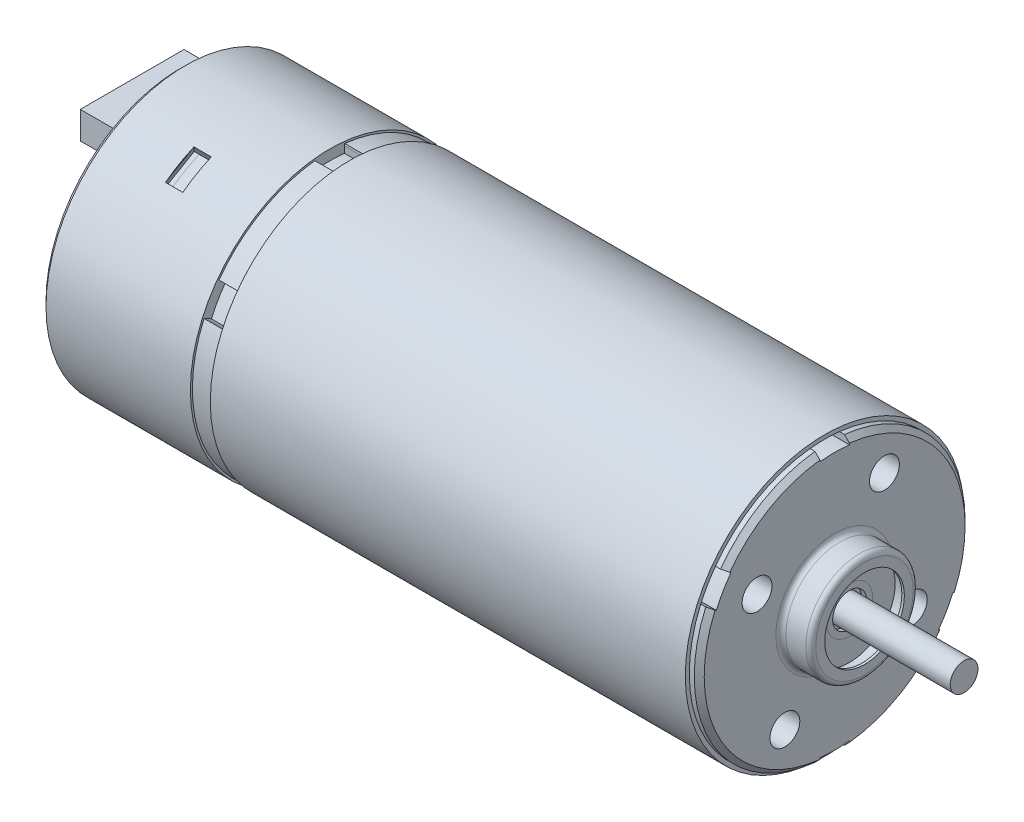
SolidWorks part; units mm, degrees
ref_plane "Front Plane" through (0, 0, 0) normal (0, 0, 1) x (1, 0, 0)
ref_plane "Top Plane" through (0, 0, 0) normal (0, 1, 0) x (1, 0, 0)
ref_plane "Right Plane" through (0, 0, 0) normal (1, 0, 0) x (0, 0, -1)
sketch "Sketch1" plane through (0, 0, 0) normal (1, 0, 0) x (0, 0, -1)
  circle A0 centre (0, 0) radius 13.6
extrude "Boss-Extrude1" add sketch "Sketch1" against normal blind 50.7
sketch "Sketch2" plane through (0, 0, 0) normal (1, 0, 0) x (0, 0, -1)
  line L0 (0, 0) -> (0, 13.6) construction
  line L1 (0, 0) -> (-13.6, 0) construction
  line L3 (-1.4767, 12.8723) -> (-1.4767, 14.3728)
  line L4 (-1.4767, 14.3728) -> (1.4767, 14.3728)
  line L5 (1.4767, 12.8723) -> (1.4767, 14.3728)
  line L6 (-1.3673, 12.8844) -> (1.4767, 14.3728) construction
  line L7 (-1.4767, 14.3728) -> (1.3673, 12.8844) construction
  line L8 (-1.4767, -14.3728) -> (1.3673, -12.8844) construction
  line L9 (-1.3673, -12.8844) -> (1.4767, -14.3728) construction
  line L10 (1.4767, -12.8723) -> (1.4767, -14.3728)
  line L11 (-1.4767, -14.3728) -> (1.4767, -14.3728)
  line L12 (-1.4767, -12.8723) -> (-1.4767, -14.3728)
  line L13 (11.8861, -5.1574) -> (13.1855, -5.9076)
  line L14 (13.1855, -5.9076) -> (11.7089, -8.4652)
  line L15 (10.4095, -7.715) -> (11.7089, -8.4652)
  line L16 (-11.8861, 5.1574) -> (-13.1855, 5.9076)
  line L17 (-11.7089, 8.4652) -> (-13.1855, 5.9076)
  line L18 (-10.4095, 7.715) -> (-11.7089, 8.4652)
  line L19 (0, 0) -> (11.7779, -6.8) construction
  line L20 (11.8419, -5.2581) -> (11.7089, -8.4652) construction
  line L21 (13.1855, -5.9076) -> (10.4746, -7.6263) construction
  line L22 (-11.7089, 8.4652) -> (-11.8419, 5.2581) construction
  line L23 (-10.4746, 7.6263) -> (-13.1855, 5.9076) construction
  circle A0 centre (0, 0) radius 13.6 construction
  arc A1 (1.4767, 12.8723) -> (-1.4767, 12.8723) centre (0, 0) ccw
  arc A2 (1.4767, -12.8723) -> (-1.4767, -12.8723) centre (0, 0) cw
  arc A3 (10.4095, -7.715) -> (11.8861, -5.1574) centre (0, 0) ccw
  arc A4 (-11.8861, 5.1574) -> (-10.4095, 7.715) centre (0, 0) cw
  point P34 (0, 0)
  dimension "D1" = 2
extrude "Cut-Extrude1" cut sketch "Sketch2" against normal through all
ref_plane "Plane1" through (-1, 0, 0) normal (1, 0, 0) x (0, 0, -1)
sketch "Sketch3" plane through (-1, 0, 0) normal (1, 0, 0) x (0, 0, -1)
  circle A0 centre (0, 0) radius 13.6
  circle A1 centre (0, 0) radius 14
extrude "Boss-Extrude2" add sketch "Sketch3" against normal blind 47.7 separate body
sketch "Sketch4" plane through (-50.7, 0, 0) normal (-1, 0, 0) x (0, 0, 1)
  circle A1 centre (0, 0) radius 14
extrude "Boss-Extrude3" add sketch "Sketch4" along normal blind 15 separate body
sketch "Sketch5" plane through (-50.7, 0, 0) normal (1, 0, 0) x (0, 0, -1)
  line L0 (1.4767, 13.5196) -> (1.4984, 13.7184)
  line L1 (-1.4767, 13.5196) -> (-1.4984, 13.7184)
  line L2 (12.4466, -5.481) -> (12.6297, -5.5616)
  line L3 (10.97, -8.0386) -> (11.1313, -8.1568)
  line L4 (1.4767, -13.5196) -> (1.4984, -13.7184)
  line L5 (-1.4767, -13.5196) -> (-1.4984, -13.7184)
  line L6 (-12.4466, 5.481) -> (-12.6297, 5.5616)
  line L7 (-10.97, 8.0386) -> (-11.1313, 8.1568)
  arc A0 (-12.4466, 5.481) -> (-1.4767, -13.5196) centre (0, 0) ccw construction
  arc A1 (1.4767, -13.5196) -> (10.97, -8.0386) centre (0, 0) ccw construction
  arc A2 (12.4466, -5.481) -> (1.4767, 13.5196) centre (0, 0) ccw construction
  arc A3 (-1.4767, 13.5196) -> (-10.97, 8.0386) centre (0, 0) ccw construction
  arc A4 (-12.4466, 5.481) -> (-1.4767, -13.5196) centre (0, 0) ccw
  arc A5 (1.4767, -13.5196) -> (10.97, -8.0386) centre (0, 0) ccw
  arc A6 (12.4466, -5.481) -> (1.4767, 13.5196) centre (0, 0) ccw
  arc A7 (-1.4767, 13.5196) -> (-10.97, 8.0386) centre (0, 0) ccw
  arc A8 (-12.6297, 5.5616) -> (-1.4984, -13.7184) centre (0, 0) ccw
  arc A9 (1.4984, -13.7184) -> (11.1313, -8.1568) centre (0, 0) ccw
  arc A10 (12.6297, -5.5616) -> (1.4984, 13.7184) centre (0, 0) ccw
  arc A11 (-1.4984, 13.7184) -> (-11.1313, 8.1568) centre (0, 0) ccw
  dimension "D1" = 0.2
extrude "Boss-Extrude4" add sketch "Sketch5" along normal up to surface (2 mm away) up to face at (-48.7, 0, -13.6)
sketch "Sketch6" plane through (0, 0, 0) normal (1, 0, 0) x (0, 0, -1)
  line L0 (-7.7942, 4.5) -> (7.7942, -4.5) construction
  line L1 (-5, -8.6603) -> (5, 8.6603) construction
  circle A0 centre (-5, -8.6603) radius 1.5
  circle A1 centre (5, 8.6603) radius 1.5
  circle A2 centre (-7.7942, 4.5) radius 1.5
  circle A3 centre (7.7942, -4.5) radius 1.5
  point P0 (0, 0)
  point P1 (0, 0)
  point P7 (0, 0)
extrude "Cut-Extrude2" cut sketch "Sketch6" against normal blind 7
sketch "Sketch7" plane through (0, 0, 0) normal (1, 0, 0) x (0, 0, -1)
  circle A0 centre (0, 0) radius 5.4
extrude "Boss-Extrude5" add sketch "Sketch7" along normal blind 3
sketch "Sketch8" plane through (3, 0, 0) normal (1, 0, 0) x (0, 0, -1)
  circle A0 centre (0, 0) radius 4
extrude "Cut-Extrude3" cut sketch "Sketch8" against normal blind 1.5
sketch "Sketch9" plane through (1.5, 0, 0) normal (1, 0, 0) x (0, 0, -1)
  circle A0 centre (0, 0) radius 1.7
extrude "Cut-Extrude4" cut sketch "Sketch9" against normal blind 0.5
sketch "Sketch10" plane through (1.5, 0, 0) normal (1, 0, 0) x (0, 0, -1)
  circle A0 centre (0, 0) radius 2.3
split line "Split Line1"
sketch "Sketch12" plane through (1.5, 0, 0) normal (1, 0, 0) x (0, 0, -1)
  circle A0 centre (0, 0) radius 4
  circle A1 centre (0, 0) radius 4.5708
extrude "Cut-Extrude5" cut sketch "Sketch12" along normal blind 1.25
fillet "Fillet1" radius 0.5 2 edges at (3, 0, -5.4) (0, 0, -5.4)
chamfer "Chamfer1" distance 0.5 angle 45 5 edges at (-65.7, 0, 14) (0, -11.7779, -6.8) (0, 6.8, -11.7779) (0, 11.7779, 6.8) (0, -6.8, 11.7779)
ref_plane "Plane2" through (0, 12.1244, 7) normal (0, 0.866, 0.5) x (1, 0, 0)
sketch "Sketch13" plane through (0, 12.1244, 7) normal (0, 0.866, 0.5) x (1, 0, 0)
  line L0 (-50.7, -5.5616) -> (-50.7, 5.5616) construction
  line L1 (-50.7, 0) -> (-65.2, 0) construction
  line L2 (-65.2, -14) -> (-65.2, 14) construction
  line L4 (-57.08, -1.6532) -> (-58.82, -1.6532)
  line L5 (-57.08, -1.6532) -> (-57.08, 1.6532)
  line L6 (-57.08, 1.6532) -> (-58.82, 1.6532)
  line L7 (-58.82, -1.6532) -> (-58.82, 1.6532)
  line L8 (-57.08, -1.6532) -> (-58.82, 1.6532) construction
  line L9 (-57.08, 1.6532) -> (-58.82, -1.6532) construction
  point P8 (-57.95, 0)
extrude "Cut-Extrude6" cut sketch "Sketch13" against normal up to surface (1.1491 mm away)
sketch "Sketch14" plane through (-58.82, 0, 0) normal (1, 0, 0) x (0, 0, -1)
  line L0 (-5.2565, 12.4109) -> (-8.1199, 10.7578)
  line L2 (-8.3827, 11.2129) -> (-7.8571, 10.3026)
  line L3 (-4.9937, 11.9558) -> (-5.5193, 12.8661)
  line L4 (-8.1199, 10.7578) -> (-7.8571, 10.3026)
  line L5 (-4.9937, 11.9558) -> (-5.2565, 12.4109)
  arc A2 (-4.9937, 11.9558) -> (-7.8571, 10.3026) centre (0, 0) ccw
  arc A3 (-5.5193, 12.8661) -> (-8.3827, 11.2129) centre (0, 0) ccw
  arc A4 (-4.9937, 11.9558) -> (-7.8571, 10.3026) centre (0, 0) ccw
  dimension "D1" = 0
extrude "Cut-Extrude7" cut sketch "Sketch14" against normal blind 0.5
sketch "Sketch15" plane through (0, 0.8266, -1.4317) normal (0, -0.5, 0.866) x (1, 0, 0)
  line L0 (-58.82, 13.902) -> (-59.32, 12.8509)
  line L1 (-58.82, 13.902) -> (-58.82, 12.8509)
  line L2 (-57.08, 12.8509) -> (-59.32, 12.8509) construction
  line L3 (-58.82, 12.8509) -> (-59.32, 12.8509)
extrude "Cut-Extrude8" cut sketch "Sketch15" along normal up to surface (3.3064 mm away) up to face at (-58.4067, 10.7578, 8.1199)
sketch "Sketch16" plane through (0, 0.8266, -1.4317) normal (0, -0.5, 0.866) x (1, 0, 0)
  line L0 (-59.07, 13.3765) -> (-59.32, 12.8509)
  line L1 (-59.32, 12.8509) -> (-59.32, 13.3765)
  line L2 (-59.32, 13.3765) -> (-59.07, 13.3765) construction
  line L3 (-59.32, 12.8509) -> (-59.32, 13.3765) construction
  line L4 (-59.32, 13.3765) -> (-59.07, 13.3765)
extrude "Boss-Extrude7" add sketch "Sketch16" along normal up to surface (3.3064 mm away) up to face at (-58.5014, 10.6927, 8.0824)
ref_plane "Plane3" through (0, 0, 0) normal (0, 0.866, 0.5) x (1, 0, 0)
mirror "Mirror1" about plane through (0, 0, 0) normal (0, 0.866, 0.5) of "Cut-Extrude7", "Cut-Extrude8", "Boss-Extrude7", "Cut-Extrude6"
sketch "Sketch17" plane through (-65.7, 0, 0) normal (-1, 0, 0) x (0, 0, 1)
  line L0 (0, 13.5) -> (0, 8.7367) construction
  line L2 (-5.2073, 7.3617) -> (5.2073, 7.3617)
  line L3 (-5.2073, 7.3617) -> (-5.2073, 10.1117)
  line L4 (-5.2073, 10.1117) -> (5.2073, 10.1117)
  line L5 (5.2073, 7.3617) -> (5.2073, 10.1117)
  line L6 (-5.2073, 7.3617) -> (5.2073, 10.1117) construction
  line L7 (-5.2073, 10.1117) -> (5.2073, 7.3617) construction
  circle A0 centre (0, 0) radius 13.5 construction
  dimension "D1" = 2.75
extrude "Boss-Extrude8" add sketch "Sketch17" along normal blind 4.85 separate body
sketch "Sketch18" plane through (-70.55, 0, 0) normal (-1, 0, 0) x (0, 0, 1)
  line L0 (-5.2073, 10.1117) -> (-5.2073, 7.3617) construction
  line L3 (5.2073, 10.1117) -> (-5.2073, 10.1117) construction
  line L4 (5.2073, 7.3617) -> (5.2073, 10.1117) construction
  line L5 (-5.2073, 7.3617) -> (5.2073, 7.3617) construction
  line L6 (-5.2073, 10.1117) -> (-5.2073, 7.3617)
  line L7 (5.2073, 10.1117) -> (-5.2073, 10.1117)
  line L8 (5.2073, 7.3617) -> (5.2073, 10.1117)
  line L9 (-5.2073, 7.3617) -> (5.2073, 7.3617)
  line L10 (-4.8073, 9.7117) -> (-4.8073, 7.7617)
  line L11 (-4.8073, 7.7617) -> (4.8073, 7.7617)
  line L12 (4.8073, 7.7617) -> (4.8073, 9.7117)
  line L13 (4.8073, 9.7117) -> (-4.8073, 9.7117)
  dimension "D1" = 0.4
extrude "Cut-Extrude10" cut sketch "Sketch18" against normal up to surface (4.85 mm away) contours L10 L11 L12 L13 up to face at (-65.7, 0, 13.5)
sketch "Sketch19" plane through (-65.7, 0, 0) normal (-1, 0, 0) x (0, 0, 1)
  line L8 (5.6073, 6.9867) -> (5.6073, 10.4867)
  line L9 (5.6073, 10.4867) -> (-5.6073, 10.4867)
  line L10 (-5.6073, 10.4867) -> (-5.6073, 6.9867)
  line L11 (-5.6073, 6.9867) -> (5.6073, 6.9867)
  line L12 (-4.8073, 8.7367) -> (0, 8.7367) construction
  line L13 (-4.8073, 9.7117) -> (-4.8073, 7.7617) construction
  line L14 (-5.6073, 10.4867) -> (5.6073, 6.9867) construction
  dimension "D1" = 3.5
split line "Split Line2"
sketch "Sketch20" plane through (-65.7, 0, 0) normal (-1, 0, 0) x (0, 0, 1)
  line L0 (0, 7.7617) -> (0, 9.7117) construction
  line L1 (-4.8073, 7.7617) -> (4.8073, 7.7617) construction
  line L2 (4.8073, 9.7117) -> (-4.8073, 9.7117) construction
  circle A0 centre (0, 8.7367) radius 0.7
  circle A2 centre (1.8, 8.7367) radius 0.7
  circle A3 centre (3.6, 8.7367) radius 0.7
  circle A4 centre (-1.8, 8.7367) radius 0.7
  circle A5 centre (-3.6, 8.7367) radius 0.7
  dimension "D1" = 1.4
  dimension "D2" = 3
  dimension "D3" = 3
extrude "Boss-Extrude9" add sketch "Sketch20" along normal up to surface (4.85 mm away) up to face at (-70.55, 8.7367, 0)
scale "Scale1" bodies to scale 122 111 scale about centroid uniform scaling yes scale factor 0.25
sketch "Sketch21" plane through (-24.4961, 0, 0) normal (1, 0, 0) x (0, 0, -1)
  circle A0 centre (0, 0) radius 0.3487
extrude "Boss-Extrude10" add sketch "Sketch21" along normal blind 3
